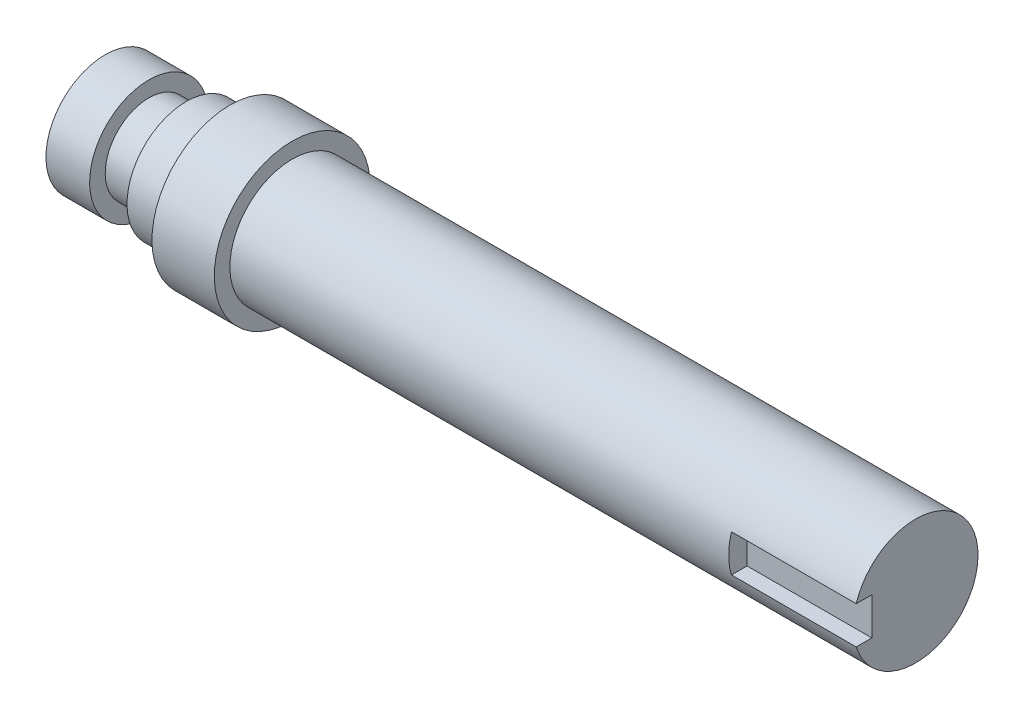
SolidWorks part; units mm, degrees
ref_plane "Front Plane" through (0, 0, 0) normal (0, 0, 1) x (1, 0, 0)
ref_plane "Top Plane" through (0, 0, 0) normal (0, 1, 0) x (1, 0, 0)
ref_plane "Right Plane" through (0, 0, 0) normal (1, 0, 0) x (0, 0, -1)
sketch "Sketch1" plane through (0, 0, 0) normal (0, 0, 1) x (1, 0, 0)
  line L0 (0, 0) -> (0, 9.5)
  line L1 (0, 9.5) -> (7, 9.5)
  line L2 (7, 9.5) -> (7, 7)
  line L3 (7, 7) -> (13, 7)
  line L4 (13, 7) -> (13, 9.5)
  line L5 (13, 9.5) -> (20, 9.5)
  line L6 (20, 9.5) -> (20, 12.5)
  line L7 (20, 12.5) -> (30, 12.5)
  line L8 (30, 12.5) -> (30, 10)
  line L9 (30, 10) -> (130, 10)
  line L10 (130, 10) -> (130, 0)
  line L11 (130, 0) -> (0, 0)
  dimension "D1" = 9.5
  dimension "D2" = 12.5
  dimension "D3" = 10
  dimension "D4" = 7
  dimension "D5" = 10
  dimension "D6" = 130
  dimension "D7" = 100
  dimension "D8" = 7
  dimension "D9" = 6
revolve "Revolve1" add sketch "Sketch1" angle 360 about L11
sketch "Sketch2" plane through (130, 0, 0) normal (1, 0, 0) x (0, 0, -1)
  line L0 (0, 0) -> (7.5711, 0) construction
  line L2 (-9.5394, 3) -> (-7.0394, 3)
  line L4 (-9.5394, -3) -> (-7.0394, -3)
  line L5 (-7.0394, 3) -> (-7.0394, -3)
  circle A1 centre (0, 0) radius 10
  arc A2 (-9.5394, 3) -> (-9.5394, -3) centre (0, 0) ccw
  dimension "D2" = 6
  dimension "D3" = 2.5
  dimension "D1" = 0
extrude "Cut-Extrude1" cut sketch "Sketch2" against normal blind 20
